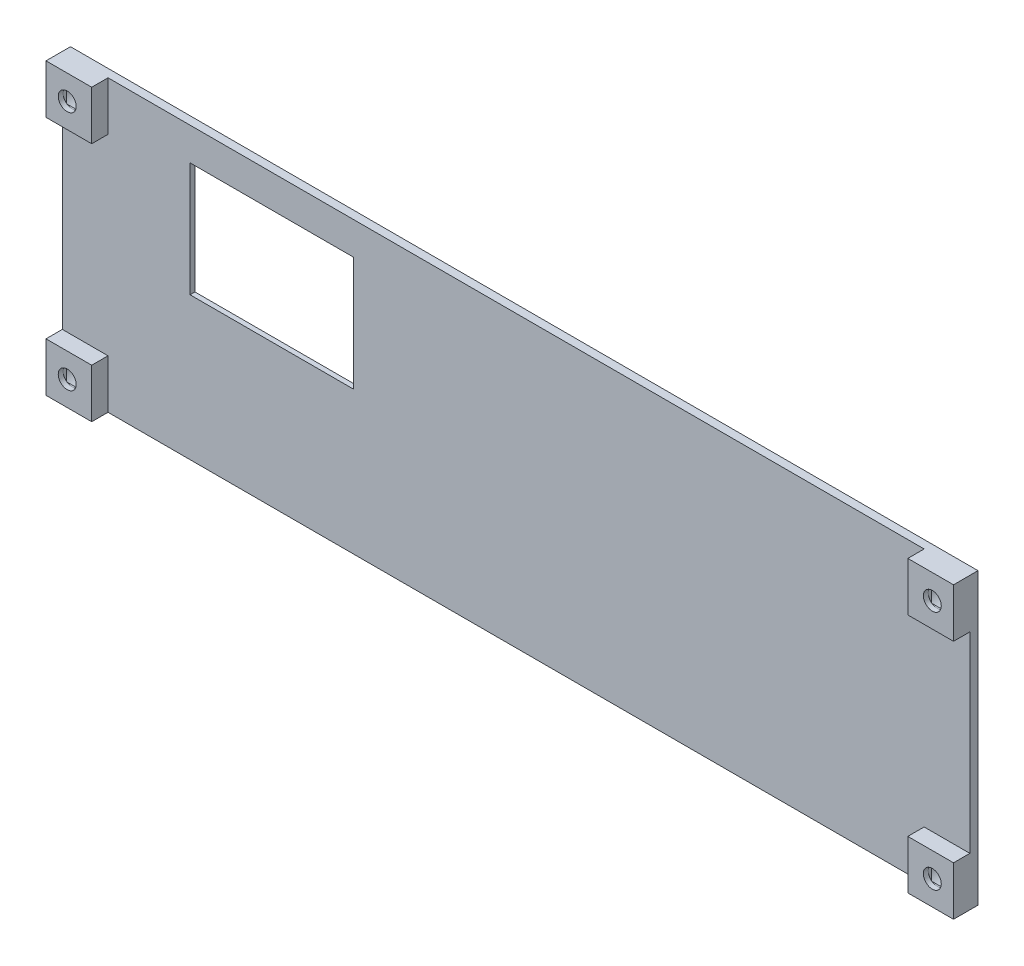
SolidWorks part; units mm, degrees
ref_plane "Front Plane" through (0, 0, 0) normal (0, 0, 1) x (1, 0, 0)
ref_plane "Top Plane" through (0, 0, 0) normal (0, 1, 0) x (1, 0, 0)
ref_plane "Right Plane" through (0, 0, 0) normal (1, 0, 0) x (0, 0, -1)
sketch "Sketch1" plane through (0, 0, 0) normal (0, 0, 1) x (1, 0, 0)
  line L1 (-56, -17.75) -> (56, -17.75)
  line L2 (-56, -17.75) -> (-56, 17.75)
  line L3 (-56, 17.75) -> (56, 17.75)
  line L4 (56, -17.75) -> (56, 17.75)
  line L5 (-56, -17.75) -> (56, 17.75) construction
  line L6 (-56, 17.75) -> (56, -17.75) construction
  point P0 (0, 0)
  dimension "D1" = 112
  dimension "D2" = 35.5
extrude "Boss-Extrude1" add sketch "Sketch1" along normal blind 1
sketch "Sketch2" plane through (0, 0, 1) normal (0, 0, 1) x (1, 0, 0)
  line L0 (0, 17.75) -> (0, -17.75) construction
  line L1 (-56, 17.75) -> (-50, 17.75)
  line L2 (-56, 17.75) -> (-56, 11.75)
  line L3 (-56, 11.75) -> (-50, 11.75)
  line L4 (-50, 17.75) -> (-50, 11.75)
  line L5 (-56, -17.75) -> (-50, -17.75)
  line L6 (-56, -17.75) -> (-56, -11.75)
  line L7 (-56, -11.75) -> (-50, -11.75)
  line L8 (-50, -17.75) -> (-50, -11.75)
  line L9 (56, 17.75) -> (-56, 17.75) construction
  line L10 (-56, -17.75) -> (56, -17.75) construction
  line L11 (50, -17.75) -> (50, -11.75)
  line L12 (56, -11.75) -> (50, -11.75)
  line L13 (56, -17.75) -> (56, -11.75)
  line L14 (56, -17.75) -> (50, -17.75)
  line L15 (50, 17.75) -> (50, 11.75)
  line L16 (56, 11.75) -> (50, 11.75)
  line L17 (56, 17.75) -> (56, 11.75)
  line L18 (56, 17.75) -> (50, 17.75)
  dimension "D1" = 6
extrude "Boss-Extrude2" add sketch "Sketch2" along normal blind 2
sketch "Sketch3" plane through (0, 0, 3) normal (0, 0, 1) x (1, 0, 0)
  line L0 (-50, 11.75) -> (-56, 17.75) construction
  line L1 (-50, -11.75) -> (-56, -17.75) construction
  line L2 (50, -11.75) -> (56, -17.75) construction
  line L3 (-56, 0) -> (56, 0) construction
  line L4 (-56, 11.75) -> (-56, -11.75) construction
  line L5 (56, -11.75) -> (56, 11.75) construction
  line L6 (0, 17.75) -> (0, -17.75) construction
  line L7 (50, 17.75) -> (-50, 17.75) construction
  line L8 (-50, -17.75) -> (50, -17.75) construction
  line L9 (50, 11.75) -> (56, 17.75) construction
  circle A0 centre (-53, 14.75) radius 1.1
  circle A1 centre (-53, -14.75) radius 1.1
  circle A2 centre (53, -14.75) radius 1.1
  circle A3 centre (53, 14.75) radius 1.1
  dimension "D1" = 2.2
extrude "Cut-Extrude1" cut sketch "Sketch3" against normal through all
sketch "Sketch4" plane through (0, 0, 0) normal (0, 0, -1) x (-1, 0, 0)
  circle A0 centre (-53, 14.75) radius 2
  circle A1 centre (-53, -14.75) radius 2
  circle A2 centre (53, 14.75) radius 2
  circle A3 centre (53, -14.75) radius 2
  dimension "D1" = 4
extrude "Cut-Extrude2" cut sketch "Sketch4" against normal blind 2
sketch "Sketch5" plane through (0, 0, 0) normal (0, 0, -1) x (-1, 0, 0)
  line L0 (-56, 17.75) -> (56, 17.75) construction
  line L1 (19.95, -0.25) -> (39.95, -0.25)
  line L2 (19.95, -0.25) -> (19.95, 13.75)
  line L3 (19.95, 13.75) -> (39.95, 13.75)
  line L4 (39.95, -0.25) -> (39.95, 13.75)
  line L5 (19.95, -0.25) -> (39.95, 13.75) construction
  line L6 (19.95, 13.75) -> (39.95, -0.25) construction
  line L7 (56, 17.75) -> (56, -17.75) construction
  point P0 (29.95, 6.75)
  dimension "D1" = 20
  dimension "D2" = 14
  dimension "D3" = 4
  dimension "D4" = 16.05
extrude "Cut-Extrude3" cut sketch "Sketch5" against normal through all
chamfer "Chamfer1" distance 0.4 angle 45 4 edges at (-29.95, 13.75, 0) (-19.95, 6.75, 0) (-29.95, -0.25, 0) (-39.95, 6.75, 0)
sketch "Sketch6" plane through (0, 0, 2) normal (0, 0, -1) x (-1, 0, 0)
  line L2 (-54.1, 13.0797) -> (-54.1, 16.4203)
  line L4 (-51.9, 13.0797) -> (-51.9, 16.4203)
  line L5 (-54.1, 13.0797) -> (-51.9, 16.4203) construction
  line L6 (-54.1, 16.4203) -> (-51.9, 13.0797) construction
  circle A0 centre (-53, 14.75) radius 2 construction
  circle A1 centre (-53, 14.75) radius 1.1 construction
  circle A2 centre (-53, 14.75) radius 2 construction
  arc A3 (-51.9, 16.4203) -> (-54.1, 16.4203) centre (-53, 14.75) ccw
  arc A4 (-54.1, 13.0797) -> (-51.9, 13.0797) centre (-53, 14.75) ccw
  point P0 (-53, 14.75)
extrude "Cut-Extrude4" cut sketch "Sketch6" against normal blind 0.2
sketch "Sketch7" plane through (0, 0, 2.2) normal (0, 0, -1) x (-1, 0, 0)
  line L0 (-51.9, 14.75) -> (-51.9, 16.4203) construction
  line L1 (-54.1, 13.65) -> (-51.9, 13.65)
  line L2 (-54.1, 13.65) -> (-54.1, 15.85)
  line L3 (-54.1, 15.85) -> (-51.9, 15.85)
  line L4 (-51.9, 13.65) -> (-51.9, 15.85)
  line L5 (-54.1, 13.65) -> (-51.9, 15.85) construction
  line L6 (-54.1, 15.85) -> (-51.9, 13.65) construction
  arc A0 (-51.9, 14.75) -> (-54.1, 14.75) centre (-53, 14.75) ccw construction
  point P0 (-53, 14.75)
extrude "Cut-Extrude5" cut sketch "Sketch7" against normal blind 0.2
mirror "Mirror1" about plane through (0, 0, 0) normal (1, 0, 0) of "Cut-Extrude4", "Cut-Extrude5"
mirror "Mirror2" about plane through (0, 0, 0) normal (0, 1, 0) of "Mirror1", "Cut-Extrude4", "Cut-Extrude5"
sketch "Sketch8" plane through (0, 0, 1) normal (0, 0, 1) x (1, 0, 0)
  line L0 (-56, -17.75) -> (-50, -17.75) construction
  line L1 (-56, 17.75) -> (-55.6, 17.75)
  line L2 (-56, 17.75) -> (-56, -17.75)
  line L3 (-56, -17.75) -> (-55.6, -17.75)
  line L4 (-55.6, 17.75) -> (-55.6, -17.75)
  line L5 (50, -17.75) -> (56, -17.75) construction
  line L6 (56, 17.75) -> (55.6, 17.75)
  line L7 (56, 17.75) -> (56, -17.75)
  line L8 (56, -17.75) -> (55.6, -17.75)
  line L9 (55.6, 17.75) -> (55.6, -17.75)
  dimension "D1" = 0.4
extrude "Cut-Extrude6" cut sketch "Sketch8" against normal through all both and the other way through all
